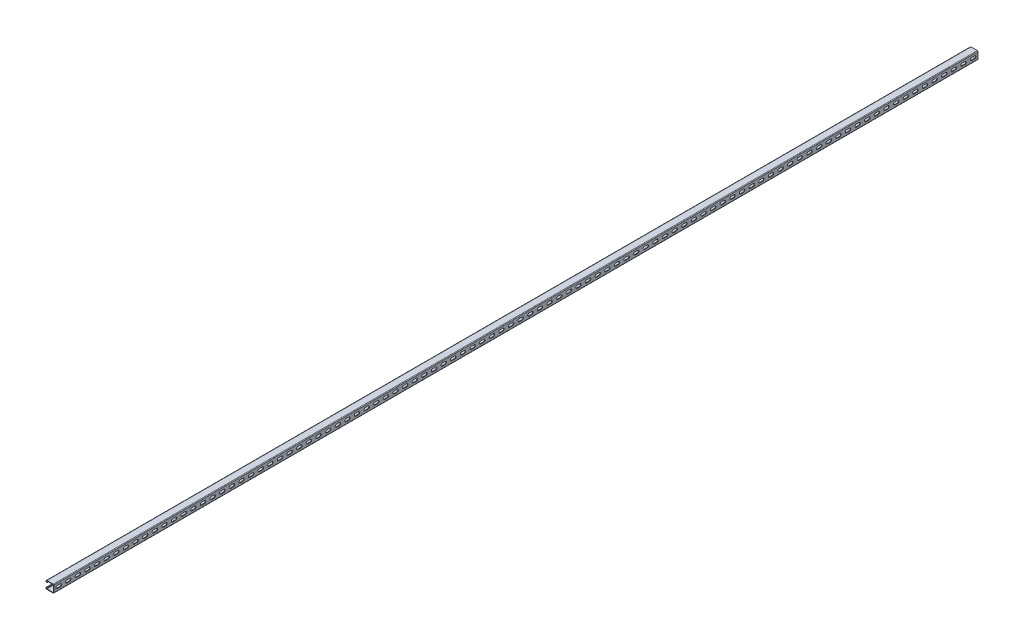
SolidWorks part; units mm, degrees
ref_plane "Front Plane" through (0, 0, 0) normal (0, 0, 1) x (1, 0, 0)
ref_plane "Top Plane" through (0, 0, 0) normal (0, 1, 0) x (1, 0, 0)
ref_plane "Right Plane" through (0, 0, 0) normal (1, 0, 0) x (0, 0, -1)
sketch "Sketch1" plane through (0, 0, 0) normal (0, 0, 1) x (1, 0, 0)
  line L0 (0, 0) -> (-41.275, 0) construction
  line L3 (-41.275, 20.6375) -> (0, 20.6375) construction
  line L4 (-41.275, 20.6375) -> (-41.275, -20.6375) construction
  line L5 (-41.275, -20.6375) -> (0, -20.6375) construction
  line L6 (0, 20.6375) -> (0, -20.6375) construction
  line L7 (-36.2267, 20.6375) -> (-3.4607, 20.6375)
  line L8 (0, 17.1767) -> (0, -17.1767)
  line L9 (-2.794, -17.1767) -> (-2.794, 17.1767)
  line L10 (-3.4608, 17.8435) -> (-36.2267, 17.8435)
  line L11 (-41.275, 15.5892) -> (-41.275, 14.5732)
  line L12 (-37.8142, 11.1125) -> (-35.5346, 11.1125)
  line L14 (-35.5346, 13.9065) -> (-37.8142, 13.9065)
  line L15 (-38.481, 14.5732) -> (-38.481, 15.5892)
  line L16 (-38.481, -14.5733) -> (-38.481, -15.5893)
  line L17 (-35.5346, -13.9065) -> (-37.8142, -13.9065)
  line L18 (-37.8142, -11.1125) -> (-35.5346, -11.1125)
  line L19 (-41.275, -15.5893) -> (-41.275, -14.5733)
  line L20 (-3.4607, -17.8435) -> (-36.2267, -17.8435)
  line L21 (-36.2267, -20.6375) -> (-3.4607, -20.6375)
  line L22 (-2.794, -20.6375) -> (-2.794, 20.6375) construction
  arc A1 (0, 17.1767) -> (-3.4607, 20.6375) centre (-3.4607, 17.1767) ccw
  arc A2 (-2.794, 17.1767) -> (-3.4608, 17.8435) centre (-3.4607, 17.1767) ccw
  arc A4 (-36.2267, 20.6375) -> (-41.275, 15.5892) centre (-36.2267, 15.5892) ccw
  arc A5 (-41.275, 14.5732) -> (-37.8142, 11.1125) centre (-37.8142, 14.5732) ccw
  arc A6 (-35.5346, 11.1125) -> (-35.5346, 13.9065) centre (-35.5346, 12.5095) ccw
  arc A7 (-37.8142, 13.9065) -> (-38.481, 14.5732) centre (-37.8142, 14.5732) cw
  arc A8 (-38.481, 15.5892) -> (-36.2267, 17.8435) centre (-36.2267, 15.5892) cw
  arc A9 (-38.481, -15.5893) -> (-36.2267, -17.8435) centre (-36.2267, -15.5893) ccw
  arc A10 (-37.8142, -13.9065) -> (-38.481, -14.5733) centre (-37.8142, -14.5733) ccw
  arc A11 (-35.5346, -11.1125) -> (-35.5346, -13.9065) centre (-35.5346, -12.5095) cw
  arc A12 (-41.275, -14.5733) -> (-37.8142, -11.1125) centre (-37.8142, -14.5733) cw
  arc A13 (-36.2267, -20.6375) -> (-41.275, -15.5893) centre (-36.2267, -15.5893) cw
  arc A14 (-2.794, -17.1767) -> (-3.4607, -17.8435) centre (-3.4607, -17.1767) cw
  arc A15 (0, -17.1767) -> (-3.4607, -20.6375) centre (-3.4607, -17.1767) cw
  point P24 (0, 20.6375)
  point P65 (-2.794, 0)
  dimension "D1" = 3.4608
  dimension "D2" = 5.0482
  dimension "D3" = 3.4608
  dimension "Ht." = 41.275
  dimension "Wd." = 41.275
  dimension "Thk." = 2.794
  dimension "D4" = 9.525
  dimension "D5" = 7.1374
extrude "Boss-Extrude1" add sketch "Sketch1" against normal blind 4876.8
sketch "Sketch3" plane through (0, 0, 0) normal (1, 0, 0) x (0, 0, -1)
  line L0 (0, 0) -> (4876.8, 0) construction
  point P2 (101.6, 0)
  point P3 (4775.2, 0)
  dimension "D1" = 101.6
  dimension "D2" = 101.6
  dimension "D3" = 4876.8
sketch "Sketch2" plane through (0, 0, 0) normal (1, 0, 0) x (0, 0, -1)
  line L0 (18.2562, 0) -> (32.5437, 0) construction
  line L1 (18.2562, 7.1438) -> (32.5437, 7.1438)
  line L2 (18.2562, -7.1438) -> (32.5437, -7.1438)
  line L3 (18.2562, 0) -> (0, 0) construction
  line L4 (25.4, 0) -> (76.2, 0) construction
  line L5 (0, -17.1767) -> (0, 17.1767) construction
  arc A0 (18.2562, 7.1438) -> (18.2562, -7.1438) centre (18.2562, 0) ccw
  arc A1 (32.5437, -7.1438) -> (32.5437, 7.1438) centre (32.5437, 0) ccw
  point P3 (25.4, 0)
  dimension "Hole to End" = 11.1125
  dimension "D2" = 25.4
extrude "Cut-Extrude1" cut sketch "Sketch2" against normal up to vertex (2.794 mm away) up to point (-2.794, 0, 0)
pattern_linear "LPattern1" count 96 spacing 50.8 along (0, 0, -1) of "Cut-Extrude1"
equation "\"D1@LPattern1\" = \"Slot Ctr.@Sketch2\""
equation "\"Hole Count@LPattern1\" = \"Lg.@Boss-Extrude1\" / \"D1@LPattern1\""
equation "\"D3@Sketch3\" = \"Lg.@Boss-Extrude1\""
